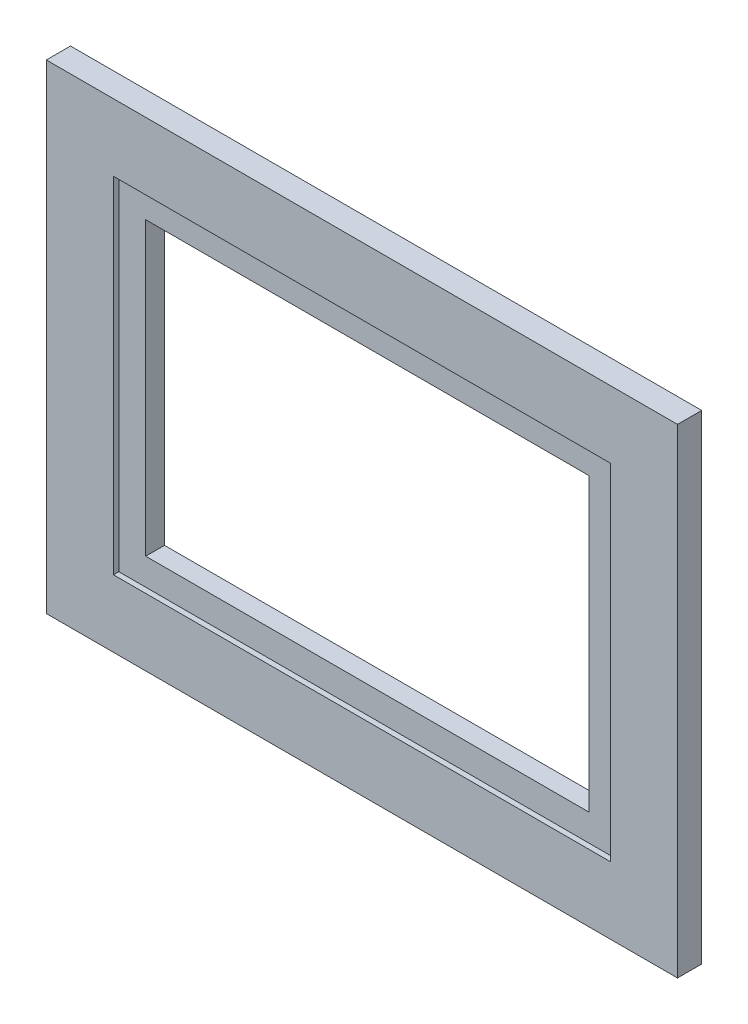
SolidWorks part; units mm, degrees
material "Teak"
ref_plane "Front Plane" through (0, 0, 0) normal (0, 0, 1) x (1, 0, 0)
ref_plane "Top Plane" through (0, 0, 0) normal (0, 1, 0) x (1, 0, 0)
ref_plane "Right Plane" through (0, 0, 0) normal (1, 0, 0) x (0, 0, -1)
sketch "Sketch1" plane through (0, 0, 0) normal (0, 0, 1) x (1, 0, 0)
  line L1 (0, 0) -> (470, 0)
  line L2 (0, 0) -> (0, 357)
  line L3 (0, 357) -> (470, 357)
  line L4 (470, 0) -> (470, 357)
  dimension "D1" = 470
  dimension "D2" = 357
extrude "Boss-Extrude1" add sketch "Sketch1" along normal blind 18
sketch "Sketch3" plane through (0, 0, 18) normal (0, 0, 1) x (1, 0, 0)
  line L8 (50, 307) -> (50, 50)
  line L9 (50, 50) -> (420, 50)
  line L10 (420, 50) -> (420, 307)
  line L11 (420, 307) -> (50, 307)
  line L12 (50, 307) -> (50, 50)
  line L13 (50, 50) -> (420, 50)
  line L14 (420, 50) -> (420, 307)
  line L15 (420, 307) -> (50, 307)
  dimension "D1" = 50
extrude "Cut-Extrude1" cut sketch "Sketch3" against normal blind 4
sketch "Sketch4" plane through (0, 0, 14) normal (0, 0, 1) x (1, 0, 0)
  line L0 (400, 287) -> (70, 287)
  line L1 (70, 287) -> (70, 70)
  line L2 (70, 70) -> (400, 70)
  line L3 (400, 70) -> (400, 287)
extrude "Cut-Extrude2" cut sketch "Sketch4" against normal through all
